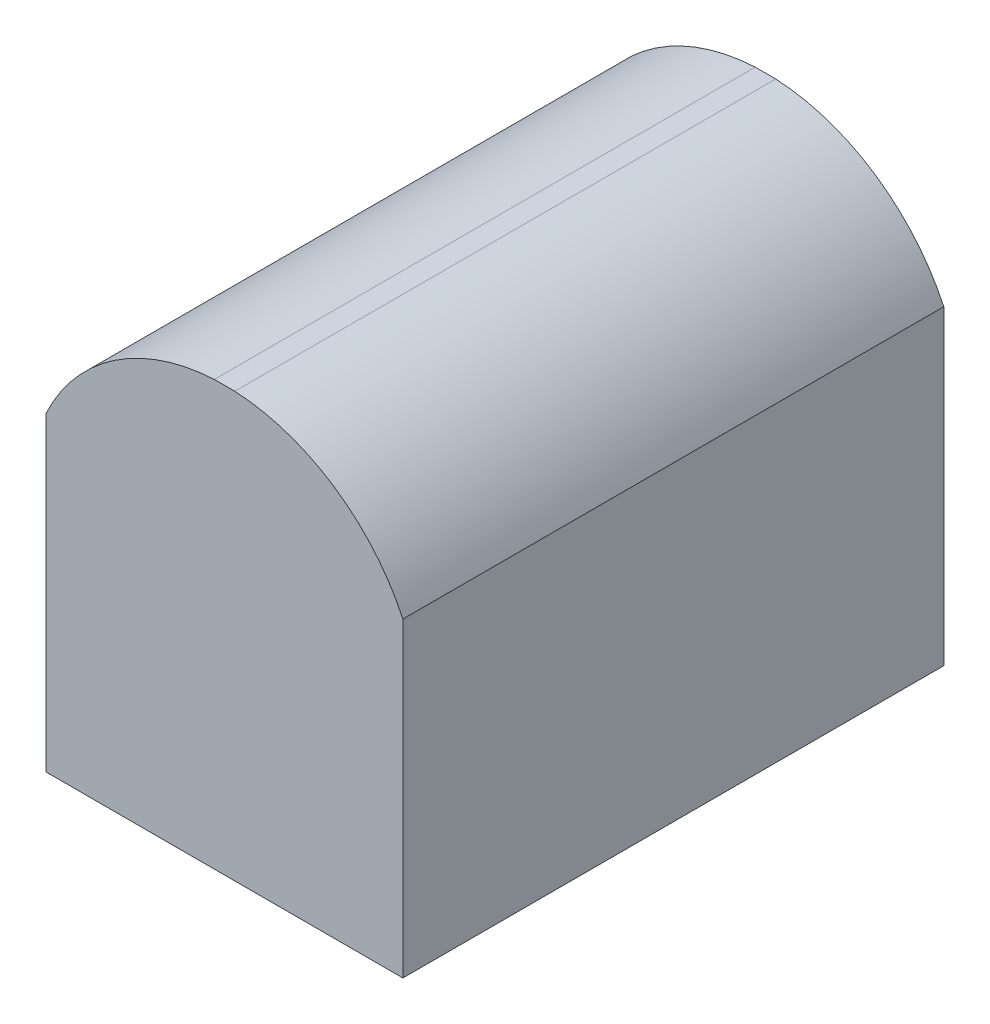
SolidWorks part; units mm, degrees
ref_plane "Front Plane" through (0, 0, 0) normal (0, 0, 1) x (1, 0, 0)
ref_plane "Top Plane" through (0, 0, 0) normal (0, 1, 0) x (1, 0, 0)
ref_plane "Right Plane" through (0, 0, 0) normal (1, 0, 0) x (0, 0, -1)
sketch "Sketch1" plane through (0, 0, 0) normal (0, 0, 1) x (1, 0, 0)
  line L0 (-10.493, 7.1634) -> (-7.7244, 7.1634)
  line L1 (-9.1087, 9.2687) -> (-9.1087, 10.4552) construction
  line L2 (-10.493, 7.1634) -> (-10.493, 9.5764)
  line L3 (-7.7244, 7.1634) -> (-7.7244, 9.5764)
  line L4 (-9.1882, 10.4552) -> (-9.0291, 10.4552)
  arc A0 (-10.493, 9.5764) -> (-9.1882, 10.4552) centre (-9.1087, 8.929) cw
  arc A1 (-9.0291, 10.4552) -> (-7.7244, 9.5764) centre (-9.1087, 8.929) cw
  dimension "D1" = 1.5282
extrude "Boss-Extrude1" add sketch "Sketch1" along normal blind 4.1986
